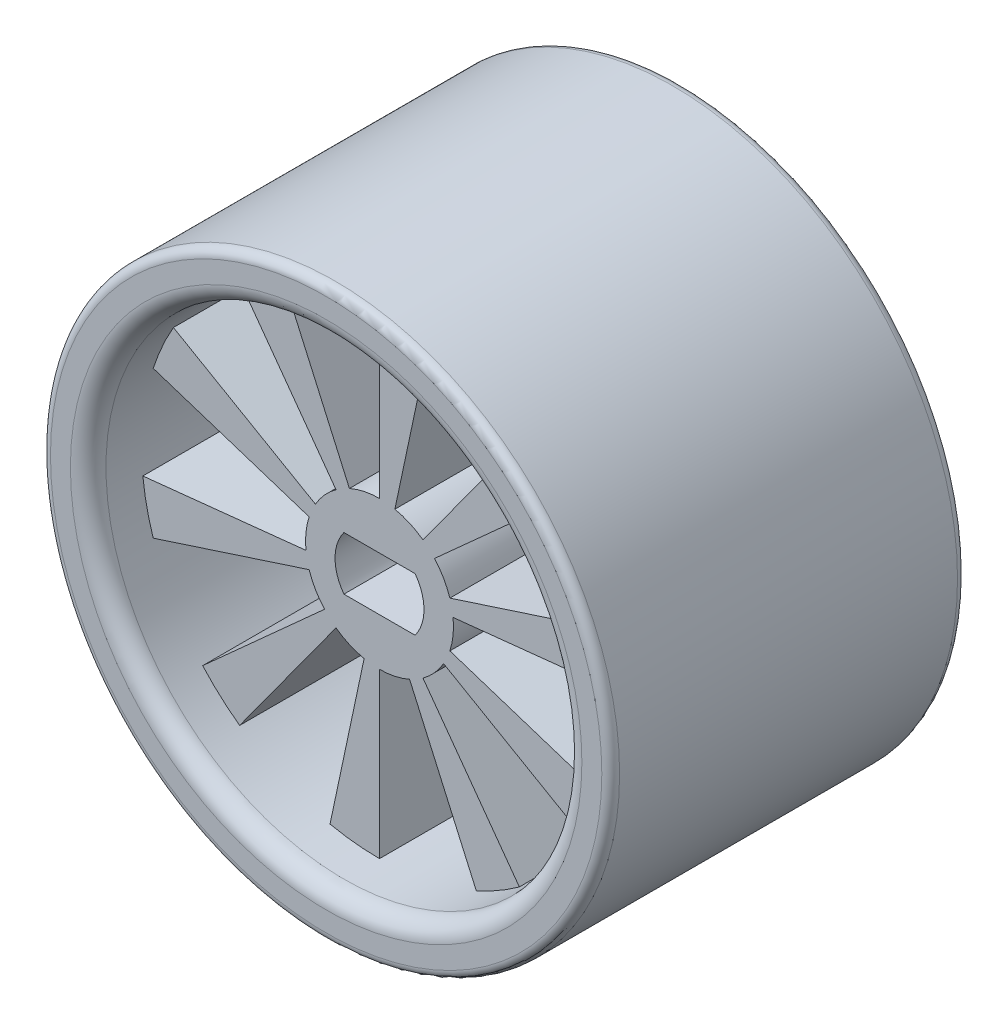
SolidWorks part; units mm, degrees
ref_plane "Front Plane" through (0, 0, 0) normal (0, 0, 1) x (1, 0, 0)
ref_plane "Top Plane" through (0, 0, 0) normal (0, 1, 0) x (1, 0, 0)
ref_plane "Right Plane" through (0, 0, 0) normal (1, 0, 0) x (0, 0, -1)
sketch "Sketch1" plane through (0, 0, 0) normal (0, 0, 1) x (1, 0, 0)
  circle A0 centre (0, 0) radius 16
  dimension "D1" = 32
extrude "Boss-Extrude1" add sketch "Sketch1" along normal blind 20
sketch "Sketch2" plane through (0, 0, 0) normal (0, 0, 1) x (1, 0, 0)
  circle A0 centre (0, 0) radius 2.5
  dimension "D1" = 5
sketch "Sketch3" plane through (0, 0, 0) normal (0, 0, 1) x (1, 0, 0)
  line L1 (-2, 1.5) -> (2, 1.5)
  line L3 (-2, -1.5) -> (2, -1.5)
  circle A0 centre (0, 0) radius 2.5 construction
  arc A1 (-2, -1.5) -> (-2, 1.5) centre (0, 0) cw
  arc A2 (2, -1.5) -> (2, 1.5) centre (0, 0) ccw
  dimension "D1" = 3
extrude "Cut-Extrude1" cut sketch "Sketch3" along normal blind 20
sketch "Sketch4" plane through (0, 0, 0) normal (0, 0, 1) x (1, 0, 0)
  line L0 (3.9557, -1.2853) -> (12.7245, -4.1345)
  line L1 (4.1365, 0.4348) -> (13.3061, 1.3985)
  line L2 (3.0909, 2.7831) -> (9.9428, 8.9525)
  line L3 (3.9557, 1.2853) -> (12.7245, 4.1345)
  line L4 (2.4448, -3.3649) -> (7.8642, -10.8241)
  line L5 (3.602, -2.0796) -> (11.5869, -6.6897)
  line L6 (0, -4.1593) -> (0, -13.3794)
  line L7 (1.6917, -3.7997) -> (5.4419, -12.2227)
  line L8 (-2.4448, -3.3649) -> (-7.8642, -10.8241)
  line L9 (-0.8648, -4.0684) -> (-2.7817, -13.087)
  line L10 (-3.9557, -1.2853) -> (-12.7245, -4.1345)
  line L11 (-3.0909, -2.7831) -> (-9.9428, -8.9525)
  line L12 (-3.9557, 1.2853) -> (-12.7245, 4.1345)
  line L13 (-4.1365, -0.4348) -> (-13.3061, -1.3985)
  line L14 (-2.4448, 3.3649) -> (-7.8642, 10.8241)
  line L16 (-3.602, 2.0796) -> (-11.5869, 6.6897)
  line L17 (0, 4.1593) -> (0, 13.3794)
  line L18 (-1.6917, 3.7997) -> (-5.4419, 12.2227)
  line L19 (2.4448, 3.3649) -> (7.8642, 10.8241)
  line L20 (0.8648, 4.0684) -> (2.7817, 13.087)
  arc A0 (3.9557, 1.2853) -> (3.0909, 2.7831) centre (0, 0) ccw
  arc A1 (12.7245, 4.1345) -> (9.9428, 8.9525) centre (0, 0) ccw
  arc A2 (3.9557, -1.2853) -> (4.1365, 0.4348) centre (0, 0) ccw
  arc A3 (12.7245, -4.1345) -> (13.3061, 1.3985) centre (0, 0) ccw
  arc A4 (2.4448, -3.3649) -> (3.602, -2.0796) centre (0, 0) ccw
  arc A5 (7.8642, -10.8241) -> (11.5869, -6.6897) centre (0, 0) ccw
  arc A6 (0, -4.1593) -> (1.6917, -3.7997) centre (0, 0) ccw
  arc A7 (0, -13.3794) -> (5.4419, -12.2227) centre (0, 0) ccw
  arc A8 (-2.4448, -3.3649) -> (-0.8648, -4.0684) centre (0, 0) ccw
  arc A9 (-7.8642, -10.8241) -> (-2.7817, -13.087) centre (0, 0) ccw
  arc A10 (-3.9557, -1.2853) -> (-3.0909, -2.7831) centre (0, 0) ccw
  arc A11 (-12.7245, -4.1345) -> (-9.9428, -8.9525) centre (0, 0) ccw
  arc A12 (-3.9557, 1.2853) -> (-4.1365, -0.4348) centre (0, 0) ccw
  arc A13 (-12.7245, 4.1345) -> (-13.3061, -1.3985) centre (0, 0) ccw
  arc A14 (-2.4448, 3.3649) -> (-3.602, 2.0796) centre (0, 0) ccw
  arc A15 (-7.8642, 10.8241) -> (-11.5869, 6.6897) centre (0, 0) ccw
  arc A16 (0, 4.1593) -> (-1.6917, 3.7997) centre (0, 0) ccw
  arc A17 (0, 13.3794) -> (-5.4419, 12.2227) centre (0, 0) ccw
  arc A18 (2.4448, 3.3649) -> (0.8648, 4.0684) centre (0, 0) ccw
  arc A19 (7.8642, 10.8241) -> (2.7817, 13.087) centre (0, 0) ccw
  point P47 (0, 0)
  dimension "D1" = 10
extrude "Cut-Extrude2" cut sketch "Sketch4" along normal blind 20
sketch "Sketch5" plane through (0, 0, 0) normal (0, 0, 1) x (1, 0, 0)
  circle A0 centre (0, 0) radius 13.3794
extrude "Cut-Extrude4" cut sketch "Sketch5" along normal blind 3
ref_plane "Plane1" through (0, 0, 20) normal (0, 0, 1) x (1, 0, 0)
sketch "Sketch6" plane through (0, 0, 20) normal (0, 0, 1) x (1, 0, 0)
  circle A0 centre (0, 0) radius 13.3794
extrude "Cut-Extrude5" cut sketch "Sketch6" against normal blind 3
fillet "Fillet1" radius 1 2 edges at (13.3794, 0, 20) (13.3794, 0, 0)
fillet "Fillet2" radius 0.5 2 edges at (16, 0, 0) (16, 0, 20)
